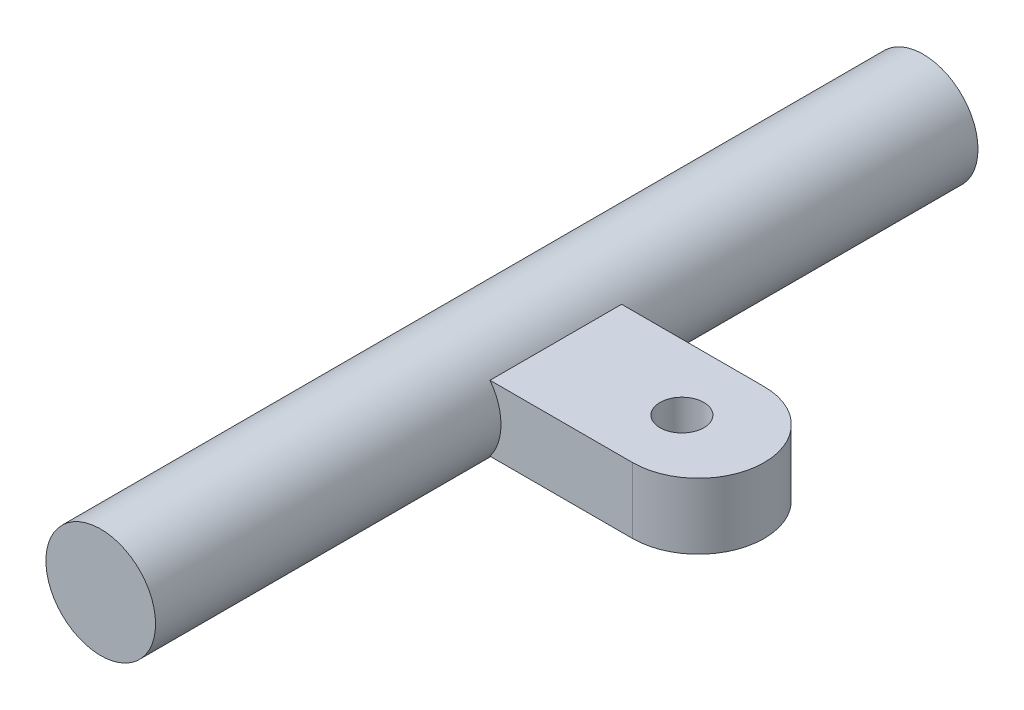
SolidWorks part; units mm, degrees
material "Plain Carbon Steel"
ref_plane "Front Plane" through (0, 0, 0) normal (0, 0, 1) x (1, 0, 0)
ref_plane "Top Plane" through (0, 0, 0) normal (0, 1, 0) x (1, 0, 0)
ref_plane "Right Plane" through (0, 0, 0) normal (1, 0, 0) x (0, 0, -1)
sketch "Sketch3" plane through (0, 0, 0) normal (0, 1, 0) x (1, 0, 0)
  line L1 (8.5, -6) -> (-8.5, -6)
  line L3 (8.5, 6) -> (-8.5, 6)
  line L4 (-8.5, -6) -> (-8.5, 6)
  line L5 (0, 6) -> (0, -6) construction
  line L6 (7, 0) -> (-8.5, 0) construction
  arc A0 (8.5, 6) -> (8.5, -6) centre (8.5, 0) cw
  circle A1 centre (7, 0) radius 2
  point P0 (0, 0)
  dimension "D3" = 4
  dimension "D1" = 12
  dimension "D2" = 17
  dimension "D4" = 7
sketch3d "3DSketch2"
  line L0 (-8.5, 0, 6) -> (-8.5, 0, -6) construction
  line L1 (7, 0, 0) -> (-8.5, 0, 0) construction
extrude "Boss-Extrude1" add sketch "Sketch3" along normal mid plane 6
sketch "Sketch4" plane through (0, 3, 0) normal (0, 1, 0) x (1, 0, 0)
  circle A0 centre (7, 0) radius 4
  dimension "D1" = 8
sketch "Sketch6" plane through (0, 0, 0) normal (0, 0, 1) x (1, 0, 0)
  line L0 (-8.5, 3) -> (-8.5, -3) construction
  circle A0 centre (-8.5, 0) radius 5
  dimension "D1" = 10
extrude "Boss-Extrude2" add sketch "Sketch6" along normal mid plane 75
sketch "Sketch8" plane through (0, 0, 37.5) normal (0, 0, 1) x (1, 0, 0)
  point P0 (-8.5, 0)
sketch3d "3DSketch3"
  line L0 (-8.5, 0, 37.5) -> (-8.5, 0, -24.3982) construction
